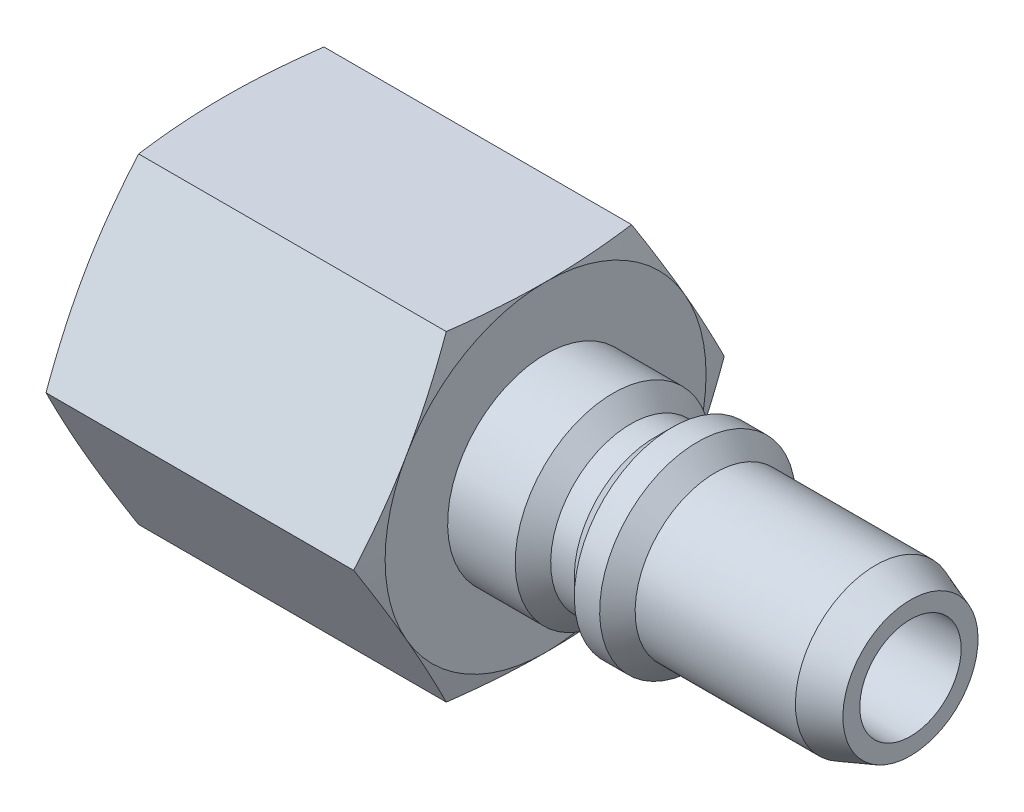
SolidWorks part; units mm, degrees
material "AISI 316 Annealed Stainless Steel Bar (SS)"
ref_plane "Front Plane" through (0, 0, 0) normal (0, 0, 1) x (1, 0, 0)
ref_plane "Top Plane" through (0, 0, 0) normal (0, 1, 0) x (1, 0, 0)
ref_plane "Right Plane" through (0, 0, 0) normal (1, 0, 0) x (0, 0, -1)
sketch "Sketch2" plane through (0, 0, 0) normal (1, 0, 0) x (0, 0, -1)
  line L1 (10.9697, 0) -> (5.4848, 9.5)
  line L2 (5.4848, 9.5) -> (-5.4848, 9.5)
  line L3 (-5.4848, 9.5) -> (-10.9697, 0)
  line L4 (-10.9697, 0) -> (-5.4848, -9.5)
  line L5 (-5.4848, -9.5) -> (5.4848, -9.5)
  line L6 (5.4848, -9.5) -> (10.9697, 0)
  circle A0 centre (0, 0) radius 9.5 construction
  circle A1 centre (0, 0) radius 3
  dimension "D2" = 6
  dimension "D1" = 19
extrude "Boss-Extrude1" add sketch "Sketch2" against normal blind 40.6
sketch "Sketch3" plane through (0, 0, 0) normal (0, 0, 1) x (1, 0, 0)
  line L0 (-40.6, 0) -> (0, 0) construction
  line L1 (-21.6, 9.5) -> (-21.6, 5.8)
  line L2 (-40.6, 9.5) -> (0, 9.5) construction
  line L3 (-21.6, 5.8) -> (-17.6, 5.8)
  line L5 (0, 9.5) -> (0, 0) construction
  line L6 (-17.6, 5.8) -> (-16.55, 4.75)
  line L7 (-16.55, 4.75) -> (-15.15, 4.75)
  line L8 (-15.15, 4.75) -> (-14.1, 5.8)
  line L9 (-11.55, 4.75) -> (-2.0606, 4.75)
  line L10 (-2.0606, 4.75) -> (0, 4)
  line L11 (-12.6, 5.8) -> (-11.55, 4.75)
  line L12 (-21.6, 9.5) -> (-22.2699, 12)
  line L13 (-22.2699, 12) -> (0, 12)
  line L14 (0, 12) -> (0, 4)
  line L15 (-14.1, 5.8) -> (-12.6, 5.8)
  line L16 (-40.6, 9.5) -> (-40.6, 13)
  line L17 (-40.6, 13) -> (-39.6622, 13)
  line L18 (-39.6622, 13) -> (-40.6, 9.5)
  dimension "D1" = 5.8
  dimension "D2" = 21.6
  dimension "D3" = 45
  dimension "D4" = 4
  dimension "D5" = 7.5
  dimension "D6" = 4.75
  dimension "D7" = 20
  dimension "D8" = 4
  dimension "D9" = 1.5
  dimension "D10" = 15
  dimension "D11" = 12
  dimension "D12" = 15
  dimension "D13" = 13
revolve "Cut-Revolve1" cut sketch "Sketch3" angle 360 about L0
hole_wizard "1/4 NPT Tapped Hole1" positions "Sketch5" profile "Sketch6" size "1/4" standard "ANSI Inch"
sketch "Sketch5" plane through (-40.6, 0, 0) normal (-1, 0, 0) x (0, 0, 1)
  point P0 (0, 0)
  dimension "D1" = 0
sketch "Sketch6" plane through (-40.6, 0, 0) normal (0, 1, 0) x (0, 0, 1)
  line L0 (0, 0) -> (0, 14.2)
  line L1 (5.5626, 14.2) -> (0, 14.2)
  line L2 (-5.5626, 14.2) -> (0, 14.2) construction
  line L3 (5.5626, 14.2) -> (5.5626, 12)
  line L4 (5.5626, 12) -> (6.5676, 12)
  line L5 (6.5676, 12) -> (6.9173, 0.3217)
  line L6 (6.9173, 0.3217) -> (7.239, 0)
  line L7 (7.239, 0) -> (0, 0)
  line L8 (0, -6.35) -> (0, 107.95) construction
  line L9 (-6.9173, 0.3217) -> (-7.239, 0) construction
  line L11 (-5.5626, 12) -> (-6.5676, 12) construction
  line L12 (-6.5676, 12) -> (-6.9173, 0.3217) construction
  dimension "Tap Drill Dia." = 11.1252
  dimension "Tap Drill Depth" = 14.2
  dimension "Thread Dia." = 13.8345
  dimension "Thread Angle" = 3.43
  dimension "Thread Depth" = 12
  dimension "C'Sink Dia." = 14.478
  dimension "C'Sink Angle" = 90
  dimension "Drill Angle" = 180
